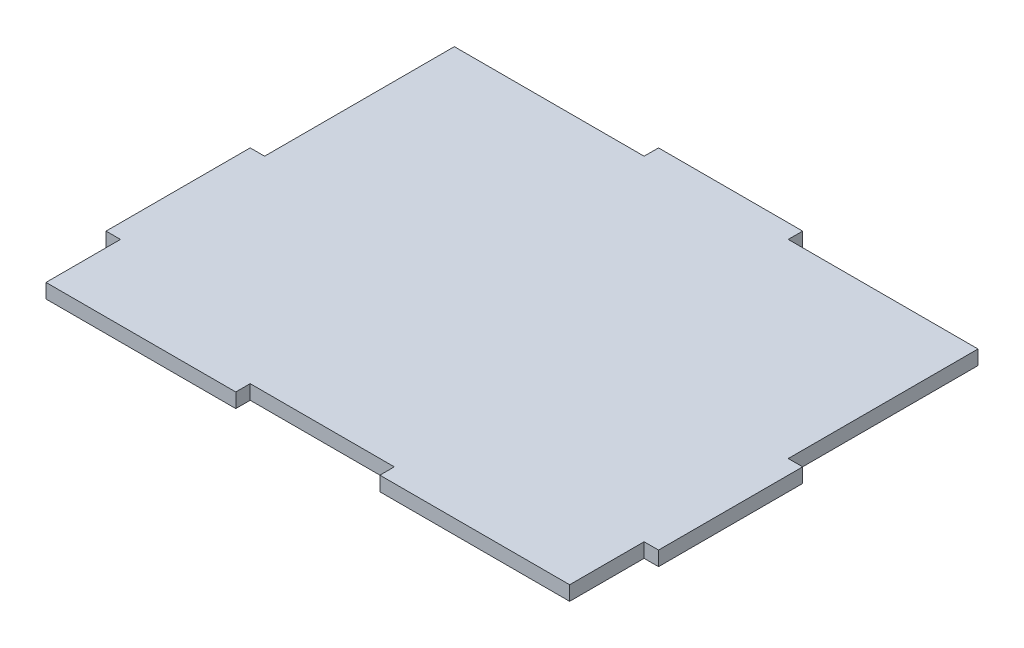
SolidWorks part; units mm, degrees
ref_plane "Front Plane" through (0, 0, 0) normal (0, 0, 1) x (1, 0, 0)
ref_plane "Top Plane" through (0, 0, 0) normal (0, 1, 0) x (1, 0, 0)
ref_plane "Right Plane" through (0, 0, 0) normal (1, 0, 0) x (0, 0, -1)
sketch "Sketch1" plane through (0, 0, 0) normal (0, 1, 0) x (1, 0, 0)
  line L0 (-57.5, 15) -> (-54.5, 15)
  line L1 (57.5, 57.5) -> (-57.5, 57.5)
  line L2 (57.5, 57.5) -> (57.5, -57.5)
  line L3 (57.5, -57.5) -> (-57.5, -57.5)
  line L4 (-57.5, 57.5) -> (-57.5, -57.5)
  line L5 (57.5, 57.5) -> (-57.5, -57.5) construction
  line L6 (57.5, -57.5) -> (-57.5, 57.5) construction
  line L7 (-54.5, 15) -> (-54.5, -15)
  line L8 (-54.5, -15) -> (-57.5, -15)
  line L9 (-15, 57.5) -> (-15, 54.5)
  line L10 (-15, 54.5) -> (15, 54.5)
  line L11 (15, 54.5) -> (15, 57.5)
  line L12 (57.5, 15) -> (54.5, 15)
  line L13 (54.5, 15) -> (54.5, -15)
  line L14 (54.5, -15) -> (57.5, -15)
  line L15 (-15, -57.5) -> (-15, -54.5)
  line L16 (-15, -54.5) -> (15, -54.5)
  line L17 (15, -54.5) -> (15, -57.5)
  line L18 (0, 57.5) -> (0, -57.5) construction
  line L19 (-57.5, 0) -> (57.5, 0) construction
  line L20 (0.2252, 54.5727) -> (0.2252, -60.4273) construction
  line L21 (-54.5, 15) -> (-54.5, 54.5)
  line L22 (-54.5, 54.5) -> (-15, 54.5)
  line L23 (15, 54.5) -> (54.5, 54.5)
  line L24 (54.5, 54.5) -> (54.5, 15)
  line L25 (54.5, -15) -> (54.5, -54.5)
  line L26 (54.5, -54.5) -> (15, -54.5)
  line L27 (-15, -54.5) -> (-54.5, -54.5)
  line L28 (-54.5, -54.5) -> (-54.5, -15)
  point P0 (0, 0)
  dimension "D1" = 115
  dimension "D2" = 115
  dimension "D3" = 3
  dimension "D4" = 30
extrude "Boss-Extrude1" add sketch "Sketch1" along normal blind 3 contours L17 L16 L15 L3 | L8 L7 L0 L4 | L10 L11 L1 L9 | L28 L27 L16 L26 L25 L13 L24 L23 L10 L22 L21 L7 | L13 L14 L2 L12
sketch "Sketch2" plane through (0, 3, 0) normal (0, 1, 0) x (1, 0, 0)
  line L0 (0, -57.5) -> (0, 57.5) construction
  line L2 (-15, -30.5) -> (-15, -27.5)
  line L3 (-15, -27.5) -> (15, -27.5)
  line L4 (15, -30.4997) -> (15, -27.5)
  line L5 (15, -57.5) -> (-15, -57.5) construction
  line L6 (15, 57.5) -> (-15, 57.5) construction
  line L7 (-15, -30.5) -> (-54.5, -30.5)
  line L8 (-54.5, -54.5) -> (-54.5, -15) construction
  line L9 (-54.5, -30.5) -> (-54.5, -57.5)
  line L10 (-54.5, -57.5) -> (54.5, -57.5)
  line L11 (54.5, -57.5) -> (54.5, -30.4997)
  line L12 (54.5, -15) -> (54.5, -54.5) construction
  line L13 (54.5, -30.4997) -> (15, -30.4997)
  point P10 (0, 0)
  point P19 (0, 0)
  dimension "D1" = 3
  dimension "D2" = 30
extrude "Cut-Extrude1" cut sketch "Sketch2" against normal blind 10
